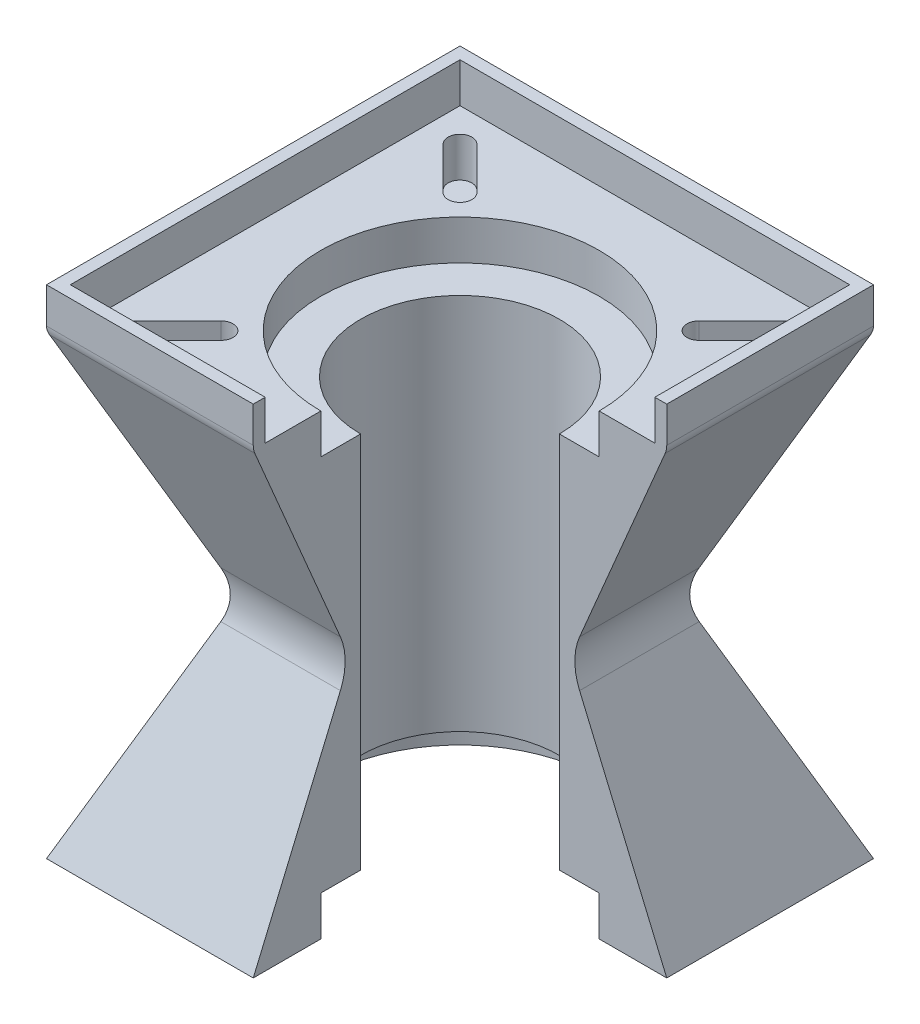
SolidWorks part; units mm, degrees
material "Cast Stainless Steel"
ref_plane "Front Plane" through (0, 0, 0) normal (0, 0, 1) x (1, 0, 0)
ref_plane "Top Plane" through (0, 0, 0) normal (0, 1, 0) x (1, 0, 0)
ref_plane "Right Plane" through (0, 0, 0) normal (1, 0, 0) x (0, 0, -1)
sketch "Sketch1" plane through (0, 0, 0) normal (0, 0, 1) x (1, 0, 0)
  line L0 (-33.6858, 0) -> (27.4083, 0) construction
  line L1 (0, 39.3952) -> (0, -7.233) construction
  line L2 (52, 57.5) -> (-52, 57.5)
  line L3 (-52, 57.5) -> (-27.5927, 0)
  line L5 (52, 57.5) -> (27.5927, 0)
  line L6 (52, -57.5) -> (27.5927, 0)
  line L7 (52, -57.5) -> (-52, -57.5)
  line L8 (-52, -57.5) -> (-27.5927, 0)
  point P10 (0, 0)
  point P12 (0, 57.5)
  dimension "D1" = 104
  dimension "D2" = 115
  dimension "D3" = 23
extrude "Boss-Extrude1" add sketch "Sketch1" along normal mid plane 104
sketch "Sketch4" plane through (0, 0, 0) normal (1, 0, 0) x (0, 0, -1)
  line L0 (-52, 57.5) -> (-27.5927, 0)
  line L1 (-52, 0) -> (52, 0) construction
  line L2 (-27.5927, 0) -> (-52, -57.5)
  line L3 (-52, -57.5) -> (-52, 0) construction
  line L4 (-52, -57.5) -> (52, -57.5) construction
  line L5 (-52, -57.5) -> (-52, 57.5)
  line L6 (0, 60.807) -> (0, -60.484) construction
  line L7 (27.5927, 0) -> (52, -57.5)
  line L8 (52, -57.5) -> (52, 57.5)
  line L9 (52, 57.5) -> (27.5927, 0)
  dimension "D1" = 23
extrude "Cut-Extrude1" cut sketch "Sketch4" against normal mid plane 104
sketch "Sketch5" plane through (0, 57.5, 0) normal (0, 1, 0) x (1, 0, 0)
  circle A0 centre (0, 0) radius 25
  dimension "D1" = 50
extrude "Cut-Extrude2" cut sketch "Sketch5" against normal through all
sketch "Sketch6" plane through (0, 57.5, 0) normal (0, 1, 0) x (1, 0, 0)
  circle A0 centre (0, 0) radius 35
  dimension "D1" = 70
extrude "Cut-Extrude4" cut sketch "Sketch6" against normal blind 10
sketch "Sketch7" plane through (0, -57.5, 0) normal (0, -1, 0) x (1, 0, 0)
  circle A0 centre (0, 0) radius 35
  dimension "D1" = 70
extrude "Cut-Extrude5" cut sketch "Sketch7" against normal blind 10
fillet "Fillet1" radius 15 4 edges at (27.5927, 0, 0) (0, 0, -27.5927) (-27.5927, 0, 0) (0, 0, 27.5927)
sketch "Sketch9" plane through (0, 57.5, 0) normal (0, 1, 0) x (1, 0, 0)
  line L0 (0, 0) -> (0, -52)
  line L1 (52, -52) -> (-52, -52) construction
  line L2 (0, -52) -> (52, -52)
  line L3 (52, -52) -> (52, 0)
  line L4 (52, -52) -> (52, 52) construction
  line L5 (52, 0) -> (0, 0)
extrude "Cut-Extrude7" cut sketch "Sketch9" against normal through all
sketch "Sketch11" plane through (0, 57.5, 0) normal (0, 1, 0) x (1, 0, 0)
  line L6 (49, 0) -> (49, 49)
  line L11 (49, 49) -> (-49, 49)
  line L12 (35, 0) -> (52, 0)
  line L13 (52, 0) -> (52, 52)
  line L14 (52, 52) -> (-52, 52)
  line L15 (-52, 52) -> (-52, -52)
  line L16 (-52, -52) -> (0, -52)
  line L17 (0, -52) -> (0, -35)
  line L18 (49, 0) -> (52, 0)
  line L19 (52, 0) -> (52, 52)
  line L20 (52, 52) -> (-52, 52)
  line L21 (-52, 52) -> (-52, -52)
  line L22 (-52, -52) -> (0, -52)
  line L23 (0, -52) -> (0, -49)
  line L24 (-49, 49) -> (-49, -49)
  line L25 (-49, -49) -> (0, -49)
  arc A2 (35, 0) -> (0, -35) centre (0, 0) ccw
  dimension "D2" = 3
  dimension "D3" = 3
  dimension "D4" = 3
  dimension "D5" = 3
  dimension "D1" = 0
extrude "Boss-Extrude2" add sketch "Sketch11" along normal blind 10
fillet "Fillet2" radius 5 4 edges at (52, 57.5, -26) (0, 57.5, -52) (-26, 57.5, 52) (-52, 57.5, 0)
sketch "Sketch15" plane through (0, 57.5, 0) normal (0, 1, 0) x (1, 0, 0)
  line L0 (0, 55.0524) -> (0, -58.8541) construction
  line L1 (-68.5779, 0) -> (81.2991, 0) construction
  line L2 (-52, -52) -> (52, 52) construction
  line L3 (-52, 52) -> (-52, -52) construction
  line L4 (-52, -52) -> (0, -52) construction
  line L5 (52, -52) -> (-52, 52) construction
  line L6 (-40.6586, 40.6586) -> (-30.052, 30.052) construction
  line L7 (-38.5373, 42.78) -> (-27.9307, 32.1734)
  line L8 (-42.78, 38.5373) -> (-32.1734, 27.9307)
  line L9 (40.6586, 40.6586) -> (30.052, 30.052) construction
  line L10 (38.5373, 42.78) -> (27.9307, 32.1734)
  line L11 (42.78, 38.5373) -> (32.1734, 27.9307)
  line L12 (-40.6586, -40.6586) -> (-30.052, -30.052) construction
  line L13 (-38.5373, -42.78) -> (-27.9307, -32.1734)
  line L14 (-42.78, -38.5373) -> (-32.1734, -27.9307)
  arc A0 (-38.5373, 42.78) -> (-42.78, 38.5373) centre (-40.6586, 40.6586) ccw
  arc A1 (-32.1734, 27.9307) -> (-27.9307, 32.1734) centre (-30.052, 30.052) ccw
  circle A2 centre (0, 0) radius 50 construction
  arc A3 (38.5373, 42.78) -> (42.78, 38.5373) centre (40.6586, 40.6586) cw
  arc A4 (32.1734, 27.9307) -> (27.9307, 32.1734) centre (30.052, 30.052) cw
  arc A5 (-38.5373, -42.78) -> (-42.78, -38.5373) centre (-40.6586, -40.6586) cw
  arc A6 (-32.1734, -27.9307) -> (-27.9307, -32.1734) centre (-30.052, -30.052) cw
  point P5 (-35.3553, 35.3553)
  point P9 (0, 0)
  point P25 (35.3553, 35.3553)
  point P32 (-35.3553, -35.3553)
  dimension "D2" = 3
  dimension "D3" = 100
  dimension "D1" = 15
extrude "Cut-Extrude12" cut sketch "Sketch15" against normal blind 10
equation "\"A\"= 115"
equation "\"B\"= 104"
equation "\"C\"= 23"
